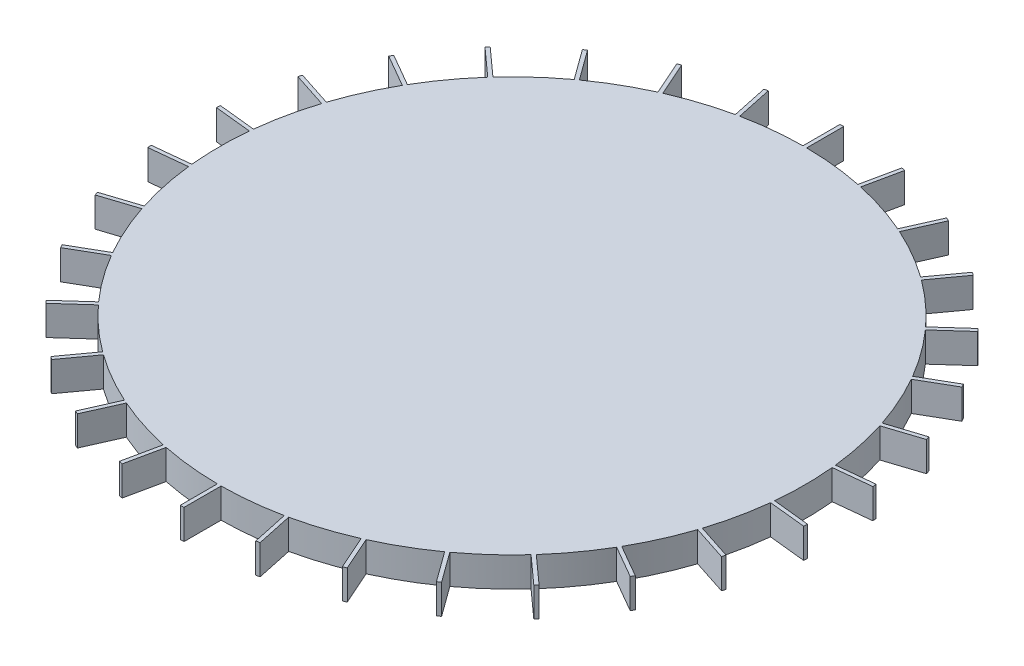
SolidWorks part; units mm, degrees
ref_plane "Front Plane" through (0, 0, 0) normal (0, 0, 1) x (1, 0, 0)
ref_plane "Top Plane" through (0, 0, 0) normal (0, 1, 0) x (1, 0, 0)
ref_plane "Right Plane" through (0, 0, 0) normal (1, 0, 0) x (0, 0, -1)
sketch "Sketch3" plane through (0, 0, 0) normal (0, 1, 0) x (1, 0, 0)
  line L1 (-0.7937, 125.41) -> (-0.7937, 141.2853)
  line L2 (0.7938, 141.2853) -> (0.7938, 125.41)
  line L3 (30.1513, 138.0328) -> (26.8506, 122.5044)
  line L4 (25.2978, 122.8345) -> (28.5985, 138.3629)
  line L5 (58.191, 128.7477) -> (51.734, 114.2449)
  line L6 (50.2837, 114.8906) -> (56.7408, 129.3934)
  line L7 (83.6876, 113.8356) -> (74.3563, 100.9923)
  line L8 (73.072, 101.9254) -> (82.4032, 114.7687)
  line L9 (105.5265, 93.9484) -> (93.7289, 83.3258)
  line L10 (92.6667, 84.5055) -> (104.4643, 95.1282)
  line L11 (122.7535, 69.9552) -> (109.0051, 62.0176)
  line L12 (108.2114, 63.3924) -> (121.9598, 71.33)
  line L13 (134.6156, 42.9046) -> (119.5173, 37.9989)
  line L14 (119.0267, 39.5087) -> (134.125, 44.4145)
  line L15 (140.5943, 13.9789) -> (124.8059, 12.3195)
  line L16 (124.64, 13.8983) -> (140.4283, 15.5577)
  line L17 (140.4283, -15.5577) -> (124.64, -13.8983)
  line L18 (124.8059, -12.3195) -> (140.5943, -13.9789)
  line L19 (134.125, -44.4145) -> (119.0267, -39.5087)
  line L20 (119.5173, -37.9989) -> (134.6156, -42.9046)
  line L21 (121.9598, -71.33) -> (108.2114, -63.3924)
  line L22 (109.0051, -62.0176) -> (122.7535, -69.9552)
  line L23 (104.4643, -95.1282) -> (92.6667, -84.5055)
  line L24 (93.7289, -83.3258) -> (105.5265, -93.9484)
  line L25 (82.4032, -114.7687) -> (73.072, -101.9254)
  line L26 (74.3563, -100.9923) -> (83.6876, -113.8356)
  line L27 (56.7408, -129.3934) -> (50.2837, -114.8906)
  line L28 (51.734, -114.2449) -> (58.191, -128.7477)
  line L29 (28.5985, -138.3629) -> (25.2978, -122.8345)
  line L30 (26.8506, -122.5044) -> (30.1513, -138.0328)
  line L31 (-0.7937, -141.2853) -> (-0.7937, -125.41)
  line L32 (0.7938, -125.41) -> (0.7938, -141.2853)
  line L33 (-30.1513, -138.0328) -> (-26.8506, -122.5044)
  line L34 (-25.2978, -122.8345) -> (-28.5985, -138.3629)
  line L35 (-58.191, -128.7477) -> (-51.734, -114.2449)
  line L36 (-50.2837, -114.8906) -> (-56.7408, -129.3934)
  line L37 (-83.6876, -113.8356) -> (-74.3563, -100.9923)
  line L38 (-73.072, -101.9254) -> (-82.4032, -114.7687)
  line L39 (-105.5265, -93.9484) -> (-93.7289, -83.3258)
  line L40 (-92.6667, -84.5055) -> (-104.4643, -95.1282)
  line L41 (-122.7535, -69.9552) -> (-109.0051, -62.0176)
  line L42 (-108.2114, -63.3924) -> (-121.9598, -71.33)
  line L43 (-134.6156, -42.9046) -> (-119.5173, -37.9989)
  line L44 (-119.0267, -39.5087) -> (-134.125, -44.4145)
  line L45 (-140.5943, -13.9789) -> (-124.8059, -12.3195)
  line L46 (-124.64, -13.8983) -> (-140.4283, -15.5577)
  line L47 (-140.4283, 15.5577) -> (-124.64, 13.8983)
  line L48 (-124.8059, 12.3195) -> (-140.5943, 13.9789)
  line L49 (-134.125, 44.4145) -> (-119.0267, 39.5087)
  line L50 (-119.5173, 37.9989) -> (-134.6156, 42.9046)
  line L51 (-121.9598, 71.33) -> (-108.2114, 63.3924)
  line L52 (-109.0051, 62.0176) -> (-122.7535, 69.9552)
  line L53 (-104.4643, 95.1282) -> (-92.6667, 84.5055)
  line L54 (-93.7289, 83.3258) -> (-105.5265, 93.9484)
  line L55 (-82.4032, 114.7687) -> (-73.072, 101.9254)
  line L56 (-74.3563, 100.9923) -> (-83.6876, 113.8356)
  line L57 (-56.7408, 129.3934) -> (-50.2837, 114.8906)
  line L58 (-51.734, 114.2449) -> (-58.191, 128.7477)
  line L59 (-28.5985, 138.3629) -> (-25.2978, 122.8345)
  line L60 (-26.8506, 122.5044) -> (-30.1513, 138.0328)
  circle A0 centre (0, 0) radius 141.2875
  arc A1 (-73.072, -101.9254) -> (-51.734, -114.2449) centre (0, 0) ccw
  arc A2 (-92.6667, -84.5055) -> (-74.3563, -100.9923) centre (0, 0) ccw
  arc A3 (-108.2114, -63.3924) -> (-93.7289, -83.3258) centre (0, 0) ccw
  arc A4 (-119.0267, -39.5087) -> (-109.0051, -62.0176) centre (0, 0) ccw
  arc A5 (-50.2837, -114.8906) -> (-26.8506, -122.5044) centre (0, 0) ccw
  arc A6 (-25.2978, -122.8345) -> (-0.7937, -125.41) centre (0, 0) ccw
  arc A7 (0.7938, -125.41) -> (25.2978, -122.8345) centre (0, 0) ccw
  arc A8 (26.8506, -122.5044) -> (50.2837, -114.8906) centre (0, 0) ccw
  arc A9 (51.734, -114.2449) -> (73.072, -101.9254) centre (0, 0) ccw
  arc A10 (74.3563, -100.9923) -> (92.6667, -84.5055) centre (0, 0) ccw
  arc A11 (93.7289, -83.3258) -> (108.2114, -63.3924) centre (0, 0) ccw
  arc A12 (109.0051, -62.0176) -> (119.0267, -39.5087) centre (0, 0) ccw
  arc A13 (119.5173, -37.9989) -> (124.64, -13.8983) centre (0, 0) ccw
  arc A14 (124.8059, -12.3195) -> (124.8059, 12.3195) centre (0, 0) ccw
  arc A15 (124.64, 13.8983) -> (119.5173, 37.9989) centre (0, 0) ccw
  arc A16 (119.0267, 39.5087) -> (109.0051, 62.0176) centre (0, 0) ccw
  arc A17 (108.2114, 63.3924) -> (93.7289, 83.3258) centre (0, 0) ccw
  arc A18 (92.6667, 84.5055) -> (74.3563, 100.9923) centre (0, 0) ccw
  arc A19 (73.072, 101.9254) -> (51.734, 114.2449) centre (0, 0) ccw
  arc A20 (50.2837, 114.8906) -> (26.8506, 122.5044) centre (0, 0) ccw
  arc A21 (25.2978, 122.8345) -> (0.7938, 125.41) centre (0, 0) ccw
  arc A22 (-0.7937, 125.41) -> (-25.2978, 122.8345) centre (0, 0) ccw
  arc A23 (-26.8506, 122.5044) -> (-50.2837, 114.8906) centre (0, 0) ccw
  arc A24 (-51.734, 114.2449) -> (-73.072, 101.9254) centre (0, 0) ccw
  arc A25 (-74.3563, 100.9923) -> (-92.6667, 84.5055) centre (0, 0) ccw
  arc A26 (-93.7289, 83.3258) -> (-108.2114, 63.3924) centre (0, 0) ccw
  arc A27 (-109.0051, 62.0176) -> (-119.0267, 39.5087) centre (0, 0) ccw
  arc A28 (-119.5173, 37.9989) -> (-124.64, 13.8983) centre (0, 0) ccw
  arc A29 (-124.8059, 12.3195) -> (-124.8059, -12.3195) centre (0, 0) ccw
  arc A30 (-124.64, -13.8983) -> (-119.5173, -37.9989) centre (0, 0) ccw
  point P128 (0, 0)
  dimension "D1" = 282.575
  dimension "D2" = 250.825
  dimension "D4" = 1.5875
  dimension "D5" = 30
extrude "Boss-Extrude1" add sketch "Sketch3" along normal blind 12.7 contours L46 A30 L43 A0 L44 A4 L41 L42 A3 L39 L40 A2 L37 L38 A1 L35 L36 A5 L33 L34 A6 L31 L32 A7 L29 L30 A8 L27 L28 A9 L25 L26 A10 L23 L24 A11 L21 L22 A12 L19
